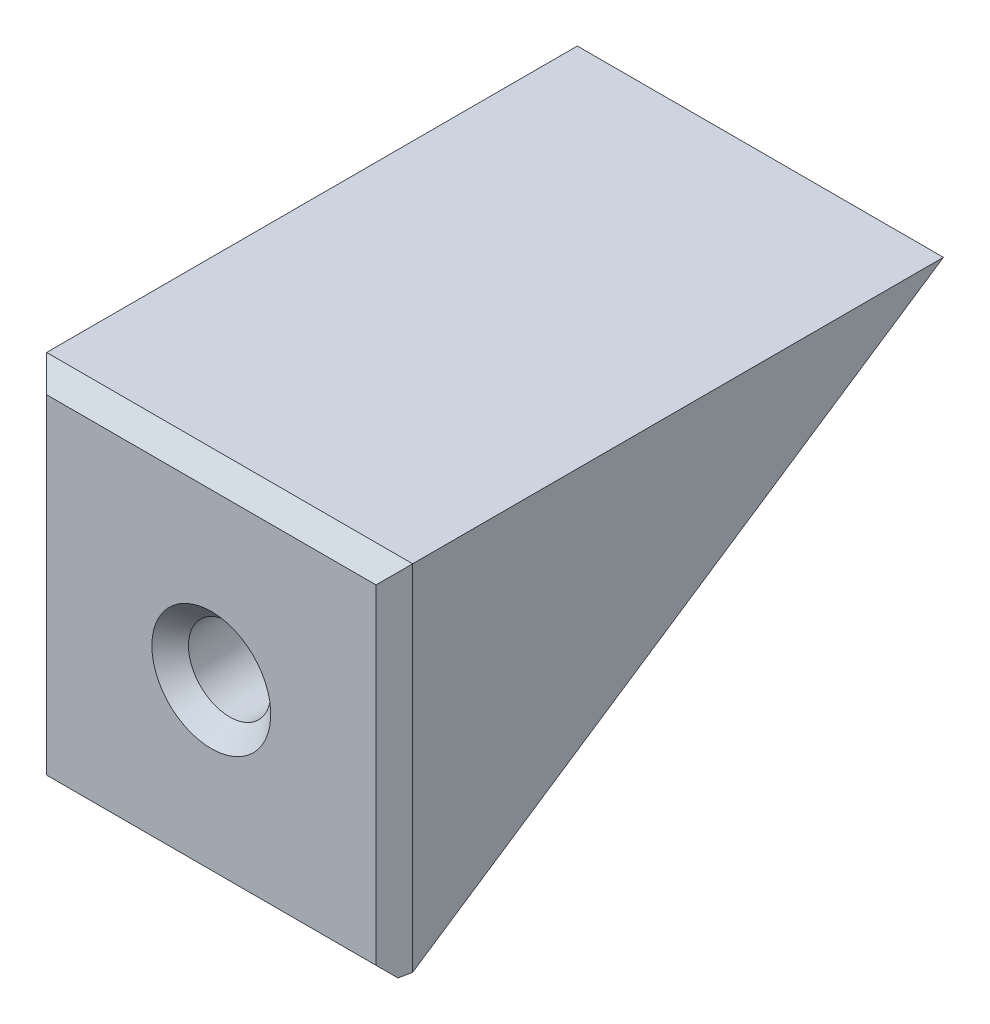
SolidWorks part; units mm, degrees
ref_plane "Front Plane" through (0, 0, 0) normal (0, 0, 1) x (1, 0, 0)
ref_plane "Top Plane" through (0, 0, 0) normal (0, 1, 0) x (1, 0, 0)
ref_plane "Right Plane" through (0, 0, 0) normal (1, 0, 0) x (0, 0, -1)
sketch "Sketch1" plane through (0, 0, 0) normal (1, 0, 0) x (0, 0, -1)
  line L0 (0, 0) -> (30, 0)
  line L1 (30, 0) -> (0, -20)
  line L2 (0, -20) -> (0, 0)
  dimension "D1" = 30
  dimension "D2" = 20
extrude "Boss-Extrude1" add sketch "Sketch1" along normal mid plane 20
ref_plane "Plane1" through (0, 0, -17) normal (0, 0, 1) x (1, 0, 0)
sketch "Sketch2" plane through (0, 0, -17) normal (0, 0, 1) x (1, 0, 0)
  line L0 (0, 0) -> (0, -20) construction
  line L1 (10, -20) -> (-10, -20) construction
  circle A0 centre (0, -10) radius 5.5
  dimension "D1" = 11
extrude "Boss-Extrude2" add sketch "Sketch2" along normal through all
sketch "Sketch3" plane through (0, 0, -17) normal (0, 0, -1) x (-1, 0, 0)
  circle A0 centre (0, -10) radius 5.5
extrude "Cut-Extrude1" cut sketch "Sketch3" along normal blind 20
hole_wizard "CSK for #8 Flat Head Machine Screw1" positions "Sketch4" profile "Sketch5" countersink size "#8" standard "ANSI Inch" end condition through all
sketch "Sketch4" plane through (0, 0, -17) normal (0, 0, -1) x (-1, 0, 0)
  point P0 (0, -10)
sketch "Sketch5" plane through (0, -10, -17) normal (1, 0, 0) x (0, 1, 0)
  line L0 (0, 0) -> (0, 17)
  line L1 (0, 17) -> (2.2479, 17)
  line L2 (2.2479, 17) -> (2.2479, 2.2645)
  line L3 (2.2479, 2.2645) -> (4.2164, 0)
  line L5 (4.2164, 0) -> (0, 0)
  line L6 (-2.2479, 2.2645) -> (-4.2164, 0) construction
  line L11 (0, -6.35) -> (0, 107.95) construction
  dimension "Thru Hole Dia." = 4.4958
  dimension "Thru Hole Depth" = 17
  dimension "Near C'Sink Dia." = 8.4328
  dimension "Near C'Sink Angle" = 82
chamfer "Chamfer1" distance 1 angle 45 5 edges at (0, -20, 0) (10, -10, 0) (0, 0, 0) (-10, -10, 0) (-2.2479, -10, 0)
